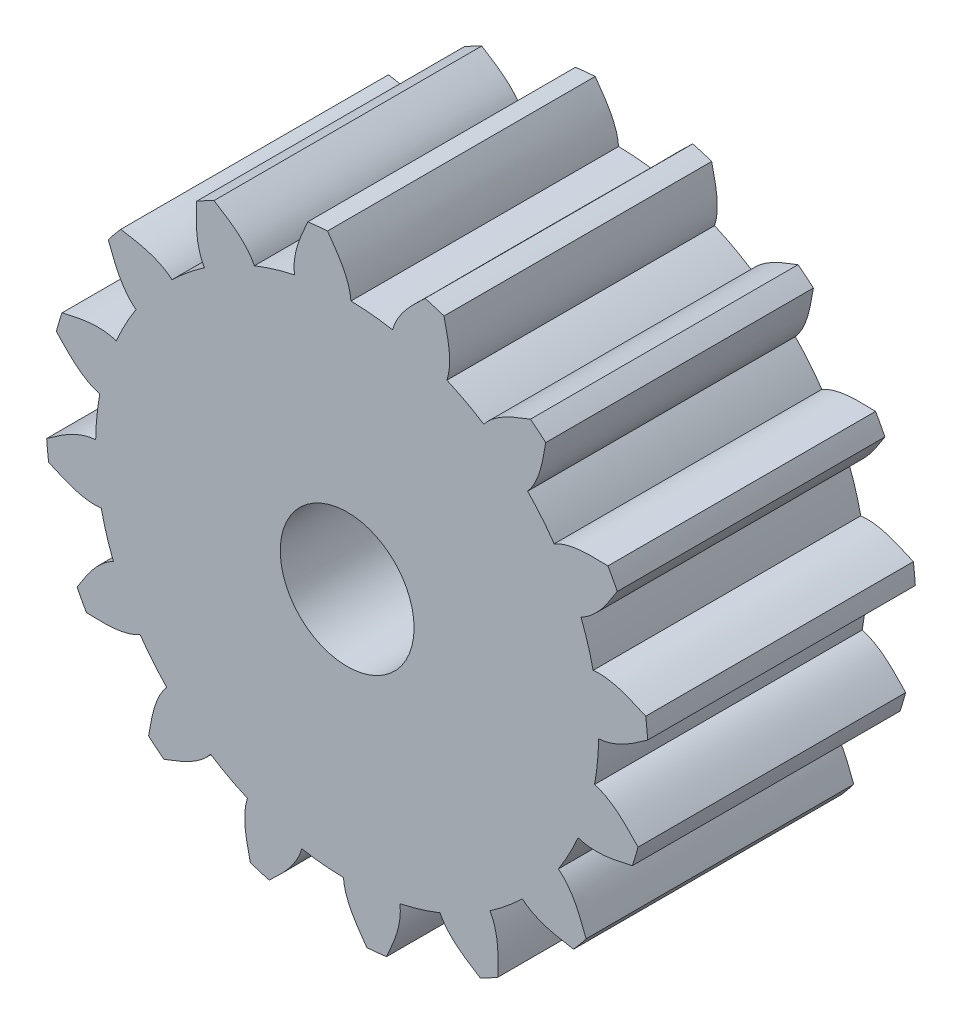
SolidWorks part; units mm, degrees
ref_plane "Front Plane" through (0, 0, 0) normal (0, 0, 1) x (1, 0, 0)
ref_plane "Top Plane" through (0, 0, 0) normal (0, 1, 0) x (1, 0, 0)
ref_plane "Right Plane" through (0, 0, 0) normal (1, 0, 0) x (0, 0, -1)
sketch "punti involuta" plane through (0, 0, 0) normal (0, 0, 1) x (1, 0, 0)
  line L0 (0, 0) -> (0, 4.6277) construction
  line L1 (-3.4916, 2) -> (3.4916, 2) construction
  line L2 (-3.4916, 0.7292) -> (3.4916, 3.2708) construction
  line L3 (0, 0) -> (-0.6428, 1.766) construction
  line L4 (-0.6428, 1.766) -> (0, 2) construction
  line L5 (-1.2414, 1.411) -> (-0.2023, 2.3252) construction
  line L6 (-0.3539, 1.8458) -> (0.0233, 1.9181) construction
  circle A0 centre (0, 0) radius 2 construction
  circle A1 centre (0, 0) radius 1.8794 construction
  arc A2 (-0.6428, 1.766) -> (-1.2414, 1.411) centre (0, 0) ccw construction
  arc A3 (-0.6428, 1.766) -> (-0.3539, 1.8458) centre (0, 0) cw construction
  arc A4 (-0.6428, 1.766) -> (0.028, 1.8792) centre (0, 0) cw construction
  point P4 (0, 2)
  point P7 (0, 2)
  dimension "D1" = 4
  dimension "D2" = 20
  dimension "D3" = 0.684
  dimension "D5" = 1.384
  dimension "D7" = 0.384
  dimension "D4" = 0.7
  dimension "D6" = 0.3
  dimension "D8" = 0.684
sketch "diametro testa" plane through (0, 0, 0) normal (0, 0, 1) x (1, 0, 0)
  circle A0 centre (0, 0) radius 2.25
  dimension "D1" = 4.5
sketch "profilo" plane through (0, 0, 0) normal (0, 0, 1) x (1, 0, 0)
  line L0 (0, 0) -> (-0.1842, 1.8703) construction
  line L1 (0, 0) -> (0, 4.6277) construction
  line L2 (-0.1842, 1.8703) -> (-0.2205, 2.2392)
  arc A1 (-0.2205, 2.2392) -> (-0.1467, 2.2452) centre (0, 0) cw
  circle A3 centre (0, 0) radius 2.25 construction
  arc A4 (0.028, 1.8792) -> (-0.1842, 1.8703) centre (0, 0) ccw
  arc A5 (0.028, 1.8792) -> (-0.6428, 1.766) centre (0, 0) ccw construction
  circle A6 centre (0, 0) radius 1.8794 construction
  spline S0 degree 3 poles (-0.2023, 2.3252) (-0.1183, 2.1969) (0.0168, 2.0487) (0.028, 1.8792) knots 0 0 0 0 1 1 1 1
  dimension "D1" = 5.625
sketch "diametro base" plane through (0, 0, 0) normal (0, 0, 1) x (1, 0, 0)
  circle A0 centre (0, 0) radius 1.8794
extrude "Boss-Extrude7" add sketch "profilo" along normal blind 2 contours S0 A1 L2 A4
ref_plane "Plane1" through (0, 0, 0) normal (0.9952, 0.098, 0) x (-0.098, 0.9952, 0)
mirror "Mirror1" about plane through (0, 0, 0) normal (0.9952, 0.098, 0) of bodies 112
pattern_circular "CirPattern1" count 16 over 360 about axis through (0, 0, 2) along (0, 0, 1) of bodies 113
extrude "Boss-Extrude9" add sketch "diametro base" along normal up to surface (2 mm away)
sketch "mozzo" plane through (0, 0, 0) normal (0, 0, 1) x (1, 0, 0)
  circle A0 centre (0, 0) radius 0.5
  dimension "D1" = 1
extrude "Cut-Extrude1" cut sketch "mozzo" along normal up to surface (2 mm away) up to face at (0, 0, 2)
equation "\"n_imposto\"= 16"
equation "\"m\"= .25"
equation "\"d_imposto\"= \"n_imposto\" * \"m\""
equation "\"alpha\"= 20"
equation "\"a1\"= .7"
equation "\"a2\"= .3"
equation "\"s\"= 2"
equation "\"D1@punti involuta\"=\"d_imposto\""
equation "\"D2@punti involuta\" = \"alpha\""
equation "\"D4@punti involuta\" = \"a1\""
equation "\"D5@punti involuta\" = \"D3@punti involuta\" + \"a1\""
equation "\"D6@punti involuta\" = \"a2\""
equation "\"D7@punti involuta\" = \"D3@punti involuta\" - \"a2\""
equation "\"D1@diametro testa\"=\"d_imposto\" + \"m\" * 2"
equation "\"D8@punti involuta\"=\"D3@punti involuta\""
equation "\"D1@profilo\"=360 / \"n_imposto\" / 4"
equation "\"D1@Boss-Extrude7\"=\"s\""
equation "\"D1@CirPattern1\"= \"n_imposto\""
equation "\"d_mozzo\"= 1"
equation "\"D1@mozzo\"=\"d_mozzo\""
